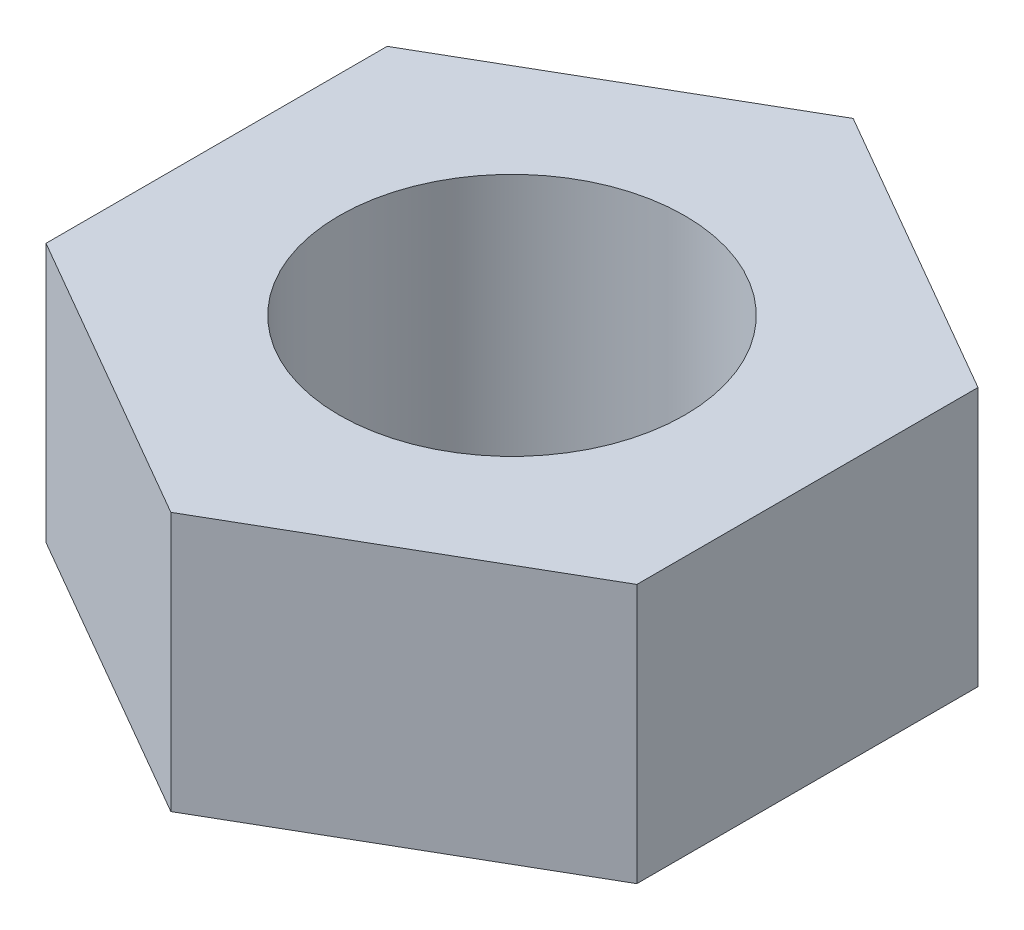
SolidWorks part; units mm, degrees
ref_plane "Front Plane" through (0, 0, 0) normal (0, 0, 1) x (1, 0, 0)
ref_plane "Top Plane" through (0, 0, 0) normal (0, 1, 0) x (1, 0, 0)
ref_plane "Right Plane" through (0, 0, 0) normal (1, 0, 0) x (0, 0, -1)
sketch "Sketch1" plane through (0, 0, 0) normal (0, 1, 0) x (1, 0, 0)
  line L1 (0, -3.9491) -> (3.42, -1.9745)
  line L2 (3.42, -1.9745) -> (3.42, 1.9745)
  line L3 (3.42, 1.9745) -> (0, 3.9491)
  line L4 (0, 3.9491) -> (-3.42, 1.9745)
  line L5 (-3.42, 1.9745) -> (-3.42, -1.9745)
  line L6 (-3.42, -1.9745) -> (0, -3.9491)
  circle A0 centre (0, 0) radius 3.42 construction
  circle A1 centre (0, 0) radius 2
  dimension "D2" = 4
  dimension "D1" = 6.84
extrude "Boss-Extrude1" add sketch "Sketch1" along normal blind 3
